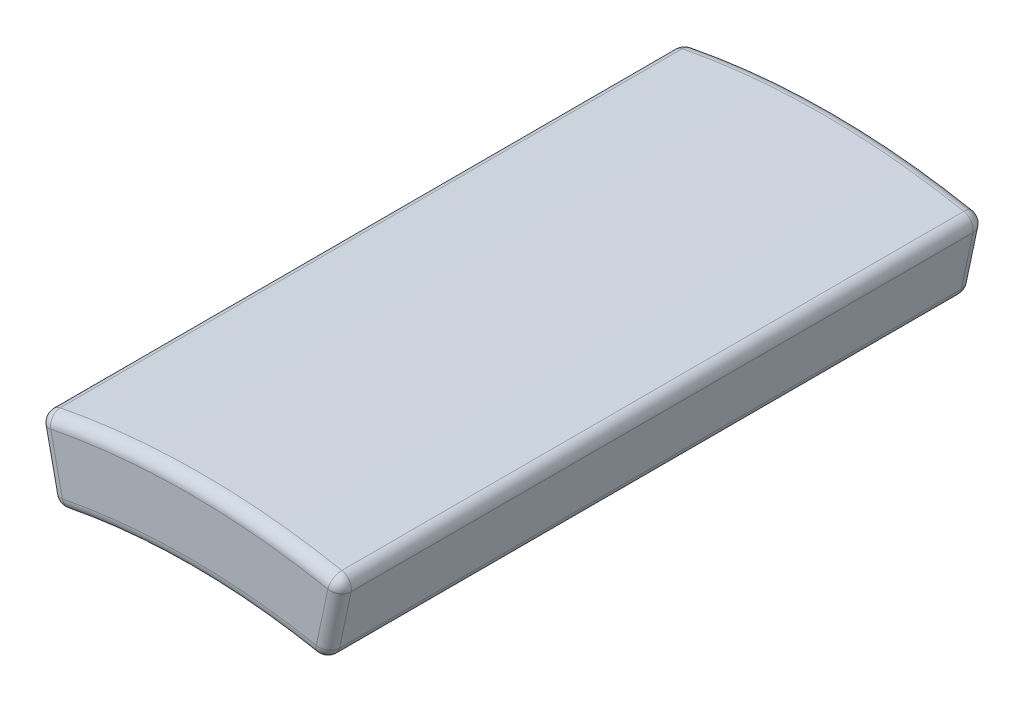
SolidWorks part; units mm, degrees
material "NdFeB N52"
ref_plane "Front Plane" through (0, 0, 0) normal (0, 0, 1) x (1, 0, 0)
ref_plane "Top Plane" through (0, 0, 0) normal (0, 1, 0) x (1, 0, 0)
ref_plane "Right Plane" through (0, 0, 0) normal (1, 0, 0) x (0, 0, -1)
sketch "Sketch4" plane through (0, 0, 0) normal (0, 0, 1) x (1, 0, 0)
  line L0 (-5.1978, 0.8037) -> (-4.6364, -1.8373)
  line L1 (4.6364, -1.8373) -> (5.1978, 0.8037)
  line L2 (0, 1.35) -> (0, -1.35) construction
  arc A0 (-4.6364, -1.8373) -> (4.6364, -1.8373) centre (0, -23.65) cw
  arc A1 (-5.1978, 0.8037) -> (5.1978, 0.8037) centre (0, -23.65) cw
  point P1 (0, 0)
  point P6 (0, -1.35)
  dimension "D3" = 22.3
  dimension "D4" = 25
  dimension "D1" = 24
  dimension "D2" = 2.7
  dimension "D5" = 9.2729
  dimension "D6" = 10.3956
extrude "Boss-Extrude2" add sketch "Sketch4" along normal mid plane 22 separate body
fillet "Fillet1" radius 0.4 12 edges at (4.6364, -1.8373, 0) (5.1978, 0.8037, 0) (-5.1978, 0.8037, 0) (-4.6364, -1.8373, 0) (-4.9171, -0.5168, 11) (0, 1.35, 11) (4.9171, -0.5168, 11) (0, -1.35, 11) (4.9171, -0.5168, -11) (0, 1.35, -11) (-4.9171, -0.5168, -11) (0, -1.35, -11)
ref_plane "CAGE ALIGNMENT" through (0, 0, 0) normal (0, 0, 1) x (1, 0, 0)
sketch "Sketch5" [suppressed] plane through (0, 0, 0) normal (0, 0, 1) x (1, 0, 0)
  line L0 (-5.3121, 1.0667) -> (-4.6364, -2.1123) construction
  line L1 (4.6364, -2.1123) -> (5.3121, 1.0667) construction
  arc A0 (-4.9743, -0.5228) -> (4.9743, -0.5228) centre (0, -23.925) cw
  arc A1 (4.6364, -2.1123) -> (-4.6364, -2.1123) centre (0, -23.925) ccw construction
split line "Magnetization split line" [suppressed]
